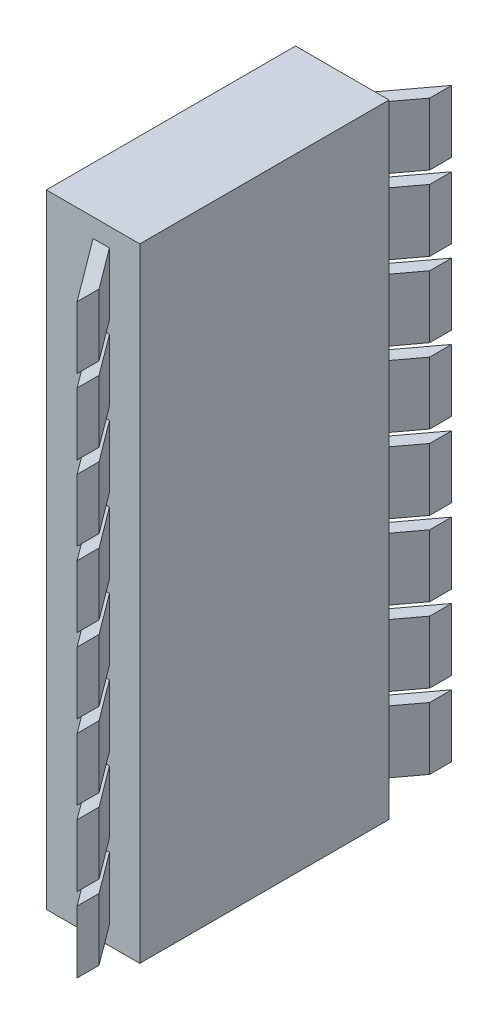
SolidWorks part; units mm, degrees
ref_plane "前视基准面" through (0, 0, 0) normal (0, 0, 1) x (1, 0, 0)
ref_plane "上视基准面" through (0, 0, 0) normal (0, 1, 0) x (1, 0, 0)
ref_plane "右视基准面" through (0, 0, 0) normal (1, 0, 0) x (0, 0, -1)
sketch "草图1" plane through (0, 0, 0) normal (1, 0, 0) x (0, 0, -1)
  line L1 (-2, -5) -> (2, -5)
  line L2 (-2, -5) -> (-2, 5)
  line L3 (-2, 5) -> (2, 5)
  line L4 (2, -5) -> (2, 5)
  line L5 (-2, -5) -> (2, 5) construction
  line L6 (-2, 5) -> (2, -5) construction
  point P0 (0, 0)
  dimension "D1" = 4
  dimension "D2" = 10
extrude "凸台-拉伸1" add sketch "草图1" along normal blind 1.5
ref_plane "基准面1" through (0, -4.7, 0) normal (0, -1, 0) x (-1, 0, 0)
sketch "草图2" plane through (0, -4.7, 0) normal (0, -1, 0) x (-1, 0, 0)
  line L0 (-0.75, 2) -> (-1.5, 3.0056)
  line L1 (-1.5, 2) -> (0, 2) construction
  line L2 (-1.5, 3.0056) -> (-1.5, 2.6532)
  line L3 (-1.5, 2.6532) -> (-1.0128, 2)
  line L4 (-1.0128, 2) -> (-0.75, 2)
extrude "凸台-拉伸2" add sketch "草图2" against normal blind 1
pattern_linear "阵列(线性)1" count 8 spacing 1.2 along (0, 1, 0) of "凸台-拉伸2"
mirror "镜向1" about plane through (0, 0, 0) normal (0, 0, 1) of "凸台-拉伸2", "阵列(线性)1"
